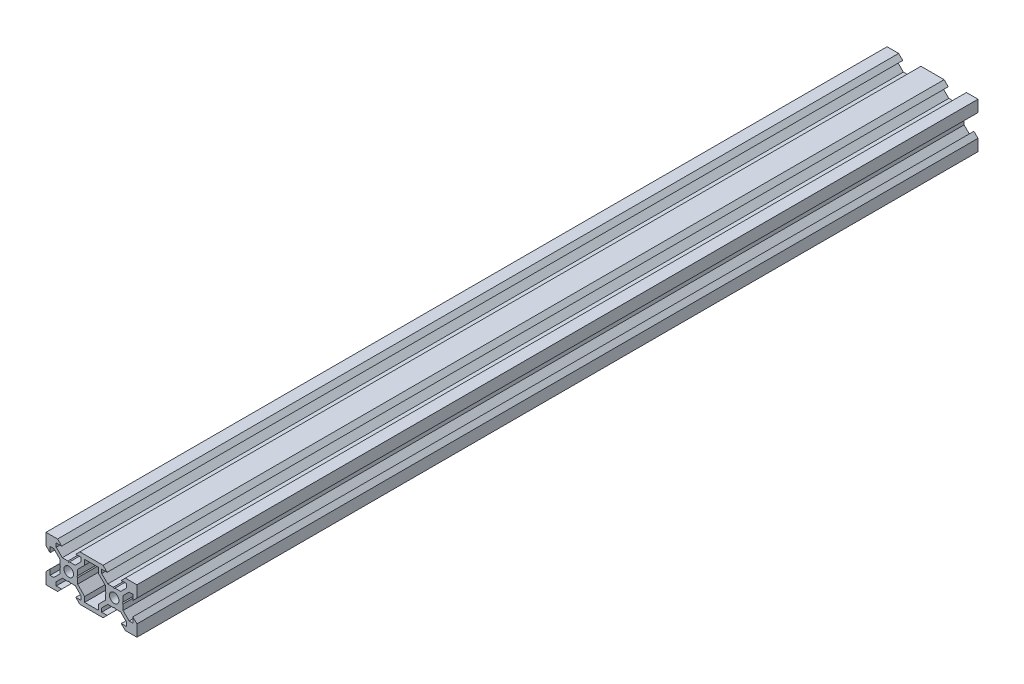
SolidWorks part; units mm, degrees
ref_plane "前视基准面" through (0, 0, 0) normal (0, 0, 1) x (1, 0, 0)
ref_plane "上视基准面" through (0, 0, 0) normal (0, 1, 0) x (1, 0, 0)
ref_plane "右视基准面" through (0, 0, 0) normal (1, 0, 0) x (0, 0, -1)
sketch "草图1" plane through (0, 0, 0) normal (0, 0, 1) x (1, 0, 0)
  line L1 (-20, 10) -> (20, 10)
  line L2 (-20, 10) -> (-20, -10)
  line L3 (-20, -10) -> (20, -10)
  line L4 (20, 10) -> (20, -10)
  line L5 (-20, 10) -> (20, -10) construction
  line L6 (-20, -10) -> (20, 10) construction
  point P0 (0, 0)
  dimension "D1" = 20
  dimension "D2" = 40
extrude "凸台-拉伸1" add sketch "草图1" against normal blind 370
sketch "草图2" plane through (0, 0, 0) normal (0, 0, 1) x (1, 0, 0)
  line L0 (0, -1000) -> (0, 49000) construction
  circle A0 centre (-10, 0) radius 2.1
  circle A1 centre (10, 0) radius 2.1
  dimension "D1" = 4.2
  dimension "D2" = 10
extrude "切除-拉伸1" cut sketch "草图2" against normal through all
sketch "草图3" plane through (0, 0, 0) normal (0, 0, 1) x (1, 0, 0)
  line L0 (10, 0) -> (35365.3391, 35355.3391) construction
  line L1 (10, 0) -> (35365.3391, -35355.3391) construction
  line L2 (16.56, 5.4993) -> (13.9007, 2.84)
  line L3 (13.9007, 2.84) -> (13.9007, 0.3536)
  line L4 (13.9007, -2.84) -> (16.56, -5.4993)
  line L5 (16.56, 5.4993) -> (18.2, 5.4993)
  line L6 (18.2, 5.4993) -> (18.2, 3.1)
  line L7 (18.2, -5.4993) -> (16.56, -5.4993)
  line L8 (-1000, 0) -> (49000, 0) construction
  line L9 (20, -10) -> (20, 10) construction
  line L10 (18.2, 3.1) -> (20, 4.9)
  line L11 (18.2, -3.1) -> (20, -4.9)
  line L12 (20, 4.9) -> (20, -4.9)
  line L13 (18.2, -3.1) -> (18.2, -5.4993)
  line L14 (13.9007, 0.3536) -> (13.5471, 0)
  line L15 (13.5471, 0) -> (13.9007, -0.3536)
  line L16 (13.9007, -0.3536) -> (13.9007, -2.84)
  point P18 (18.2, 3.1)
  point P20 (18.2, -3.1)
  dimension "D1" = 5.68
  dimension "D2" = 1.8
  dimension "D3" = 1.5
  dimension "D4" = 1.64
  dimension "D5" = 6.2
  dimension "D6" = 0.5
extrude "切除-拉伸2" cut sketch "草图3" against normal through all
pattern_circular "阵列(圆周)1" count 4 over 360 about axis through (10, 0, 0) along (0, 0, 1) of "切除-拉伸2"
mirror "镜向1" about plane through (0, 0, 0) normal (1, 0, 0) of "阵列(圆周)1", "切除-拉伸2"
sketch "草图4" plane through (0, 0, 0) normal (0, 0, 1) x (1, 0, 0)
  line L0 (-6.9, 8.2) -> (-4.5007, 8.2) construction
  line L1 (-3.0007, -8.2) -> (3.0007, -8.2)
  line L2 (-3.0007, -8.2) -> (-3.0007, -5.9387)
  line L3 (-3.0007, 8.2) -> (3.0007, 8.2)
  line L4 (3.0007, -8.2) -> (3.0007, -5.9387)
  line L5 (-3.0007, -8.2) -> (3.0007, 8.2) construction
  line L6 (-3.0007, 8.2) -> (3.0007, -8.2) construction
  line L8 (-6.0993, 2.84) -> (-3.0007, 5.9387)
  line L9 (-6.0993, 2.84) -> (-6.0993, -2.84)
  line L10 (-6.0993, -2.84) -> (-3.0007, -5.9387)
  line L11 (6.0993, 2.84) -> (3.0007, 5.9387)
  line L12 (6.0993, 2.84) -> (6.0993, -2.84)
  line L13 (6.0993, -2.84) -> (3.0007, -5.9387)
  line L15 (-6.0993, 2.84) -> (-3.44, 5.4993) construction
  line L16 (-3.44, -5.4993) -> (-6.0993, -2.84) construction
  line L17 (6.0993, 2.84) -> (3.44, 5.4993) construction
  line L18 (3.44, -5.4993) -> (6.0993, -2.84) construction
  line L19 (-3.0007, 5.9387) -> (-3.0007, 8.2)
  line L20 (3.0007, 5.9387) -> (3.0007, 8.2)
  line L21 (-4.5007, 8.2) -> (-4.5007, 6.56) construction
  point P0 (0, 0)
  point P30 (-4.5007, 7.38)
  dimension "D1" = 1.5
extrude "切除-拉伸3" cut sketch "草图4" against normal through all
